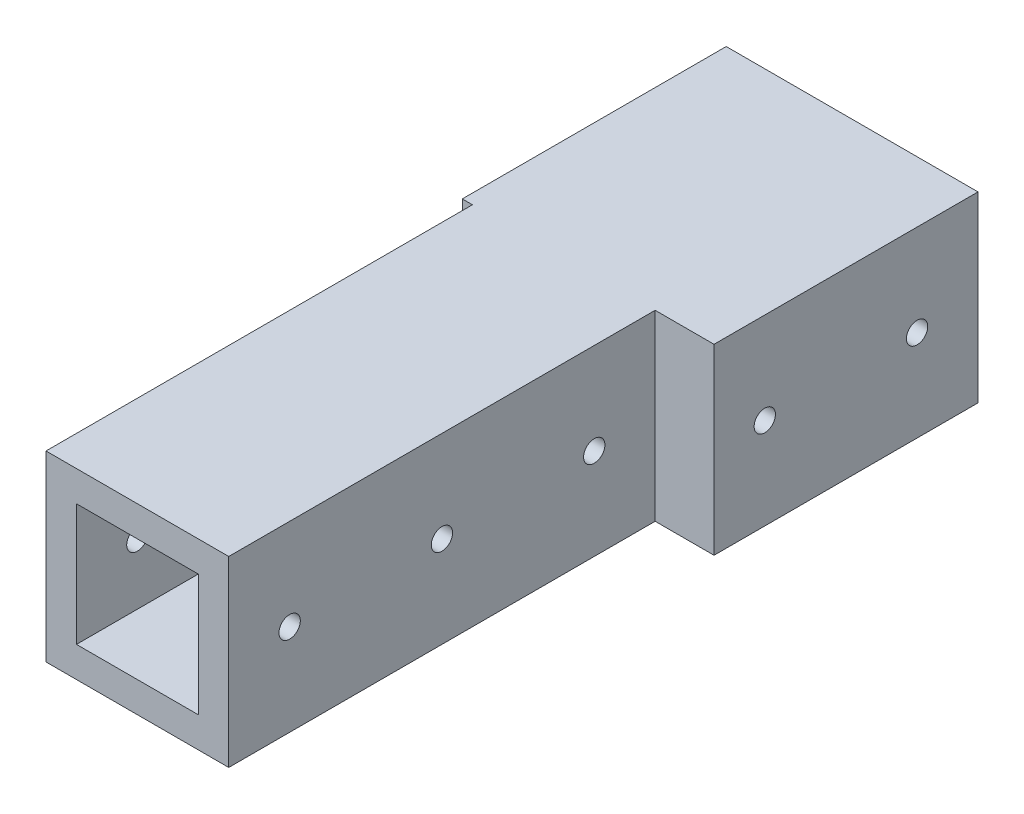
SolidWorks part; units mm, degrees
ref_plane "前视基准面" through (0, 0, 0) normal (0, 0, 1) x (1, 0, 0)
ref_plane "上视基准面" through (0, 0, 0) normal (0, 1, 0) x (1, 0, 0)
ref_plane "右视基准面" through (0, 0, 0) normal (1, 0, 0) x (0, 0, -1)
sketch "草图1" plane through (0, 0, 0) normal (0, 0, 1) x (1, 0, 0)
  line L1 (0, 0) -> (18, 0)
  line L2 (0, 0) -> (0, -18)
  line L3 (0, -18) -> (18, -18)
  line L4 (18, 0) -> (18, -18)
  line L5 (3, -3) -> (15, -3)
  line L6 (3, -3) -> (3, -15)
  line L7 (3, -15) -> (15, -15)
  line L8 (15, -3) -> (15, -15)
  dimension "D1" = 18
  dimension "D2" = 18
  dimension "D3" = 12
  dimension "D4" = 12
  dimension "D5" = 3
  dimension "D6" = 3
extrude "凸台-拉伸1" add sketch "草图1" along normal blind 68
sketch "草图2" plane through (18, 0, 0) normal (1, 0, 0) x (0, 0, -1)
  line L0 (-68, 0) -> (0, 0) construction
  line L1 (-68, -18) -> (-68, 0) construction
  circle A0 centre (-62, -9) radius 1.05
  circle A1 centre (-47, -9) radius 1.05
  circle A2 centre (-32, -9) radius 1.05
  circle A3 centre (-6, -9) radius 1.05
  circle A4 centre (-21, -9) radius 1.05
  dimension "D1" = 9
  dimension "D2" = 6
  dimension "D5" = 2.1
  dimension "D3" = 3
  dimension "D4" = 2
extrude "切除-拉伸1" cut sketch "草图2" against normal blind 32
sketch "草图3" plane through (18, 0, 0) normal (1, 0, 0) x (0, 0, -1)
  line L0 (-68, 0) -> (0, 0) construction
  line L1 (-26, 0) -> (0, 0)
  line L2 (-26, 0) -> (-26, -18)
  line L3 (-26, -18) -> (0, -18)
  line L4 (0, 0) -> (0, -18)
  circle A0 centre (-21, -9) radius 1.05 construction
  dimension "D1" = 5
extrude "凸台-拉伸2" add sketch "草图3" along normal blind 5.8
sketch "草图4" plane through (0, 0, 0) normal (-1, 0, 0) x (0, 0, 1)
  line L0 (68, -18) -> (0, -18) construction
  line L1 (0, 0) -> (26, 0)
  line L2 (0, 0) -> (0, -18)
  line L3 (0, -18) -> (26, -18)
  line L4 (26, 0) -> (26, -18)
  circle A0 centre (21, -9) radius 1.05 construction
  dimension "D1" = 5
extrude "凸台-拉伸3" add sketch "草图4" along normal blind 1
sketch "草图5" plane through (23.8, 0, 0) normal (1, 0, 0) x (0, 0, -1)
  line L0 (0, 0) -> (-26, 0) construction
  line L1 (0, -18) -> (0, 0) construction
  circle A0 centre (-6, -9) radius 1.05
  circle A2 centre (-21, -9) radius 1.05
  dimension "D1" = 2
  dimension "D2" = 9
  dimension "D3" = 6
extrude "切除-拉伸2" cut sketch "草图5" against normal blind 41
